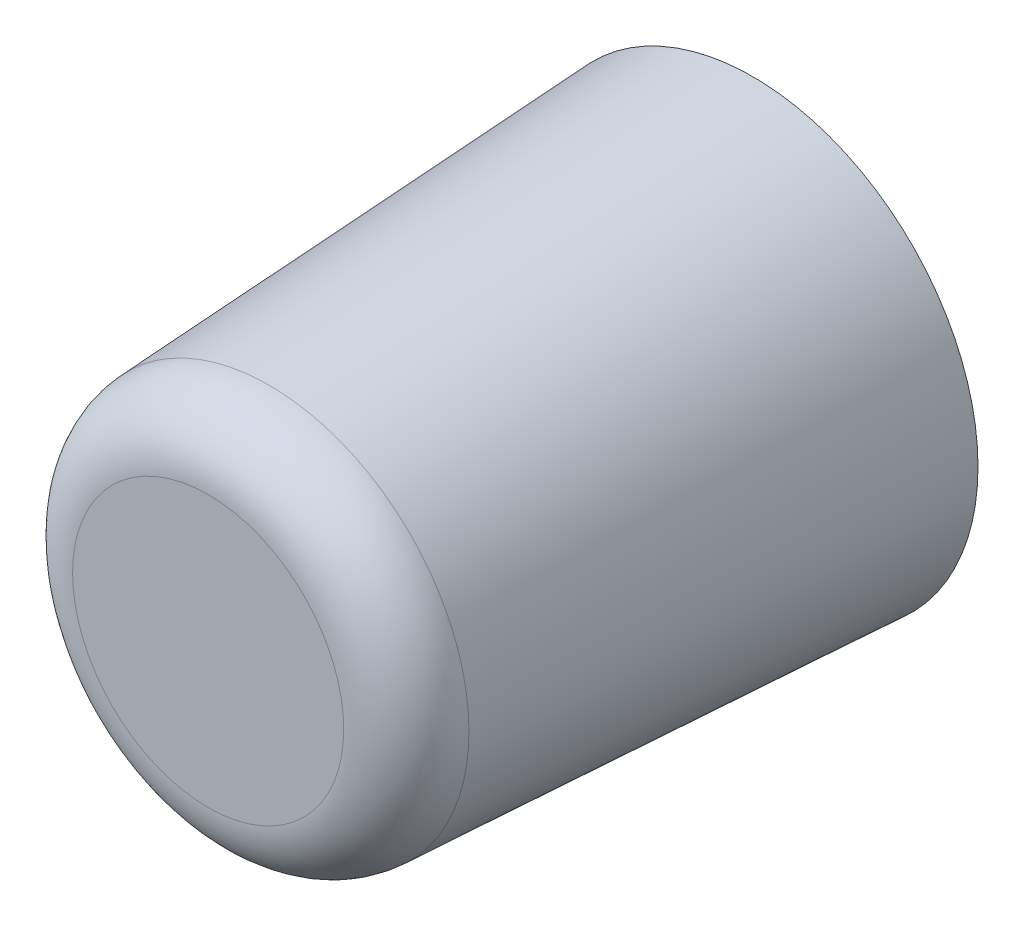
SolidWorks part; units mm, degrees
ref_plane "Front Plane" through (0, 0, 0) normal (0, 0, 1) x (1, 0, 0)
ref_plane "Top Plane" through (0, 0, 0) normal (0, 1, 0) x (1, 0, 0)
ref_plane "Right Plane" through (0, 0, 0) normal (1, 0, 0) x (0, 0, -1)
sketch "Sketch1" plane through (0, 0, 0) normal (0, 0, 1) x (1, 0, 0)
  circle A0 centre (0, 0) radius 10.5
  dimension "D1" = 21
extrude "Boss-Extrude1" add sketch "Sketch1" along normal blind 25.4 draft 3
fillet "Fillet1" radius 3 1 edges at (9.1688, 0, 25.4)
